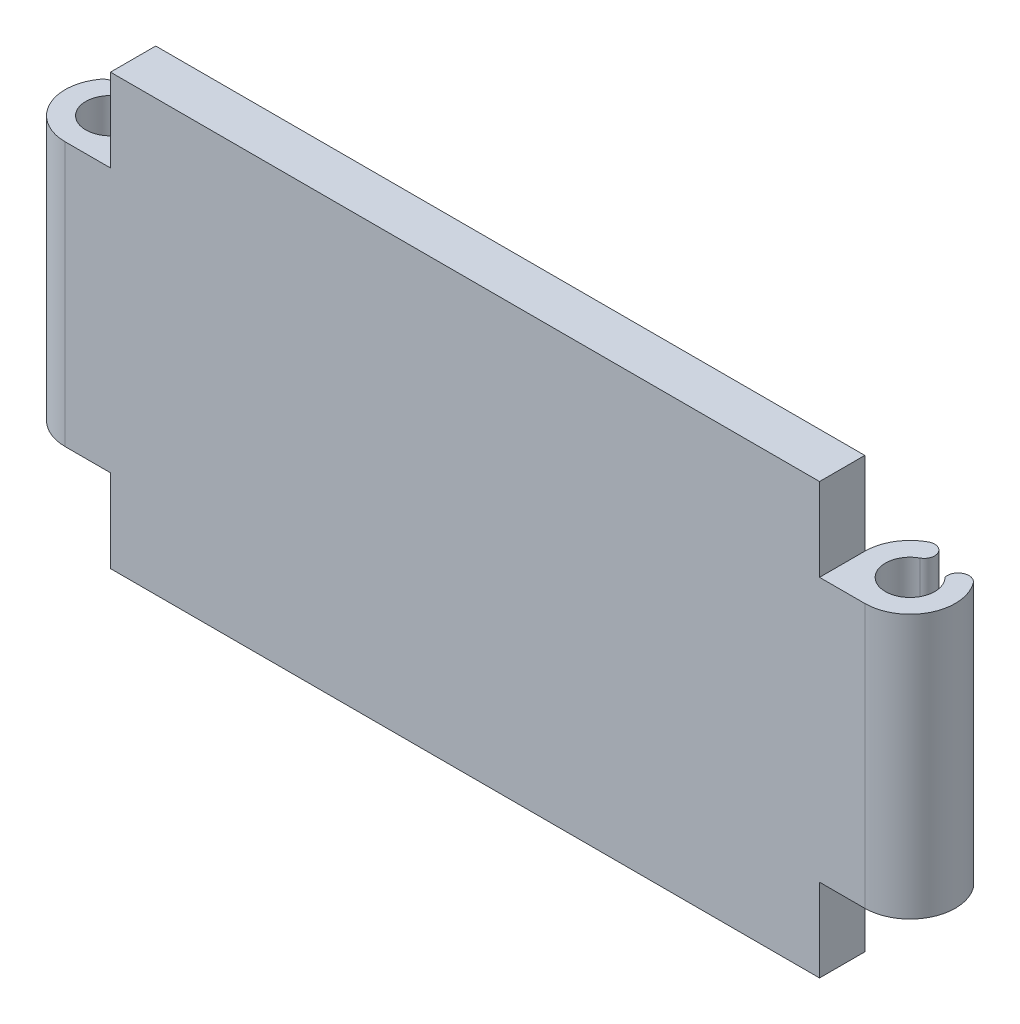
SolidWorks part; units mm, degrees
ref_plane "Plano frontal" through (0, 0, 0) normal (0, 0, 1) x (1, 0, 0)
ref_plane "Plano superior" through (0, 0, 0) normal (0, 1, 0) x (1, 0, 0)
ref_plane "Plano direito" through (0, 0, 0) normal (1, 0, 0) x (0, 0, -1)
sketch "Esboço1" plane through (0, 0, 0) normal (0, 1, 0) x (1, 0, 0)
  line L0 (-47, 0) -> (47, 0)
  line L2 (53, -6) -> (-53, -6)
  line L3 (0, 0) -> (0, -6) construction
  arc A0 (-55.2962, 2.3351) -> (-51.4496, 2.8847) centre (-53, 0) ccw
  arc A1 (-47, 0) -> (-50.1595, 5.285) centre (-53, 0) ccw
  arc A2 (-57.8639, 3.5132) -> (-53, -6) centre (-53, 0) ccw
  arc A3 (-55.2962, 2.3351) -> (-57.8639, 3.5132) centre (-56.6966, 2.6701) ccw
  arc A4 (-51.4496, 2.8847) -> (-50.1595, 5.285) centre (-50.8045, 4.0849) cw
  arc A5 (51.4496, 2.8847) -> (50.1595, 5.285) centre (50.8045, 4.0849) ccw
  arc A6 (55.2962, 2.3351) -> (57.8639, 3.5132) centre (56.6966, 2.6701) cw
  arc A7 (57.8639, 3.5132) -> (53, -6) centre (53, 0) cw
  arc A8 (47, 0) -> (50.1595, 5.285) centre (53, 0) cw
  arc A9 (55.2962, 2.3351) -> (51.4496, 2.8847) centre (53, 0) cw
  dimension "D1" = 6.55
  dimension "D2" = 12
  dimension "D4" = 3.8467
  dimension "D3" = 53
  dimension "D5" = 2.825
  dimension "D6" = 2.4003
extrude "Ressalto-extrusão1" add sketch "Esboço1" along normal blind 57
sketch "Esboço2" plane through (0, 57, 0) normal (0, 1, 0) x (1, 0, 0)
  line L0 (47, 0) -> (47, -6)
  line L1 (-53, -6) -> (53, -6) construction
  line L2 (53, -6) -> (47, -6)
  line L3 (-47, 0) -> (-47, -6)
  line L4 (-47, -6) -> (-53, -6)
  arc A0 (-47, 0) -> (-53, -6) centre (-53, 0) ccw
  arc A1 (53, -6) -> (47, 0) centre (53, 0) ccw
extrude "Corte-extrusão1" cut sketch "Esboço2" against normal blind 11
sketch "Esboço3" plane through (0, 0, 0) normal (0, -1, 0) x (1, 0, 0)
  line L0 (-47, 0) -> (-47, 6)
  line L1 (-53, 6) -> (53, 6) construction
  line L2 (-53, 6) -> (-47, 6)
  line L3 (47, 0) -> (47, 6)
  line L4 (47, 6) -> (53, 6)
  arc A0 (-53, 6) -> (-47, 0) centre (-53, 0) ccw
  arc A1 (47, 0) -> (53, 6) centre (53, 0) ccw
extrude "Corte-extrusão2" cut sketch "Esboço3" against normal blind 11
